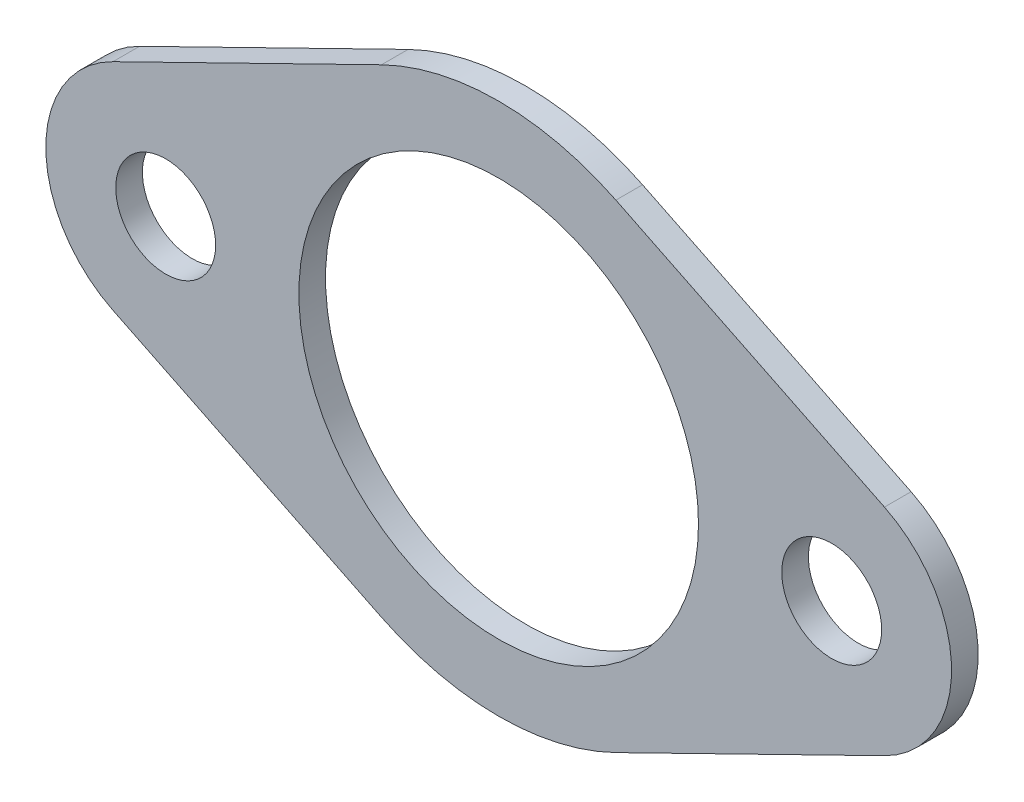
SolidWorks part; units mm, degrees
ref_plane "Front Plane" through (0, 0, 0) normal (0, 0, 1) x (1, 0, 0)
ref_plane "Top Plane" through (0, 0, 0) normal (0, 1, 0) x (1, 0, 0)
ref_plane "Right Plane" through (0, 0, 0) normal (1, 0, 0) x (0, 0, -1)
sketch "Sketch1" plane through (0, 0, 0) normal (0, 0, 1) x (1, 0, 0)
  line L0 (-22.352, 45.6183) -> (-73.5584, 20.5282)
  line L1 (-22.352, -45.6183) -> (-73.5584, -20.5282)
  line L2 (22.352, -45.6183) -> (73.5584, -20.5282)
  line L4 (73.5584, 20.5282) -> (22.352, 45.6183)
  circle A1 centre (0, 0) radius 38.1
  arc A2 (-73.5584, 20.5282) -> (-73.5584, -20.5282) centre (-63.5, 0) ccw
  arc A3 (73.5584, -20.5282) -> (73.5584, 20.5282) centre (63.5, 0) ccw
  arc A4 (-22.352, -45.6183) -> (22.352, -45.6183) centre (0, 0) ccw
  circle A5 centre (-63.5, 0) radius 9.525
  circle A6 centre (63.5, 0) radius 9.525
  arc A8 (22.352, 45.6183) -> (-22.352, 45.6183) centre (0, 0) ccw
  dimension "D3" = 19.05
  dimension "D4" = 45.72
  dimension "D5" = 45.72
  dimension "D6" = 101.6
  dimension "D7" = 76.2
  dimension "D1" = 63.5
  dimension "D2" = 63.5
  dimension "D8" = 127
extrude "Boss-Extrude1" add sketch "Sketch1" along normal blind 5.08 contours L4 A8 L0 A2 L1 A4 L2 A3 | A5 | A1 | A6
